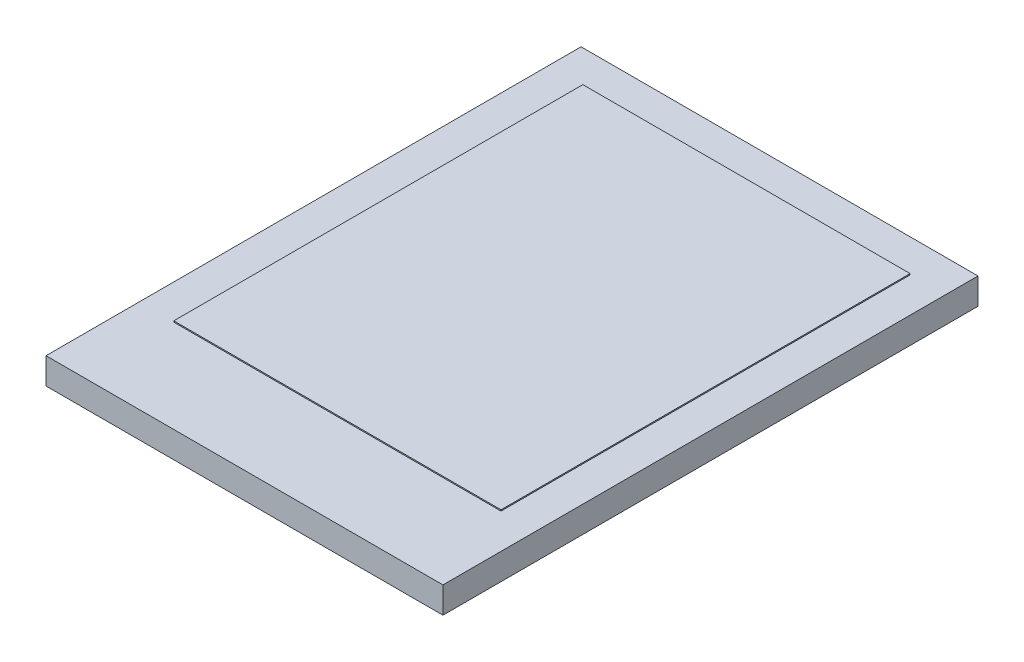
SolidWorks part; units mm, degrees
ref_plane "Спереди" through (0, 0, 0) normal (0, 0, 1) x (1, 0, 0)
ref_plane "Сверху" through (0, 0, 0) normal (0, 1, 0) x (1, 0, 0)
ref_plane "Справа" through (0, 0, 0) normal (1, 0, 0) x (0, 0, -1)
sketch "Эскиз1" plane through (0, 0, 0) normal (0, 1, 0) x (1, 0, 0)
  line L1 (-17, 22.915) -> (17, 22.915)
  line L2 (-17, 22.915) -> (-17, -22.915)
  line L3 (-17, -22.915) -> (17, -22.915)
  line L4 (17, 22.915) -> (17, -22.915)
  line L5 (-17, 22.915) -> (17, -22.915) construction
  line L6 (-17, -22.915) -> (17, 22.915) construction
  point P0 (0, 0)
  dimension "D1" = 34
  dimension "D2" = 45.83
extrude "Бобышка-Вытянуть1" add sketch "Эскиз1" along normal blind 2.25
sketch "Эскиз2" plane through (0, 2.25, 0) normal (0, 1, 0) x (1, 0, 0)
  line L0 (17, 22.915) -> (-17, 22.915) construction
  line L1 (-14.015, 20.085) -> (14.015, 20.085)
  line L2 (-14.015, 20.085) -> (-14.015, -14.955)
  line L3 (-14.015, -14.955) -> (14.015, -14.955)
  line L4 (14.015, 20.085) -> (14.015, -14.955)
  line L5 (-17, 22.915) -> (-17, -22.915) construction
  line L6 (17, -22.915) -> (17, 22.915) construction
  dimension "D1" = 2.83
  dimension "D2" = 35.04
  dimension "D3" = 28.03
  dimension "D4" = 2.985
  dimension "D5" = 2.985
extrude "Бобышка-Вытянуть2" add sketch "Эскиз2" along normal blind 0.1 contours L2 L1 L4 L3
sketch "Эскиз4" plane through (0, 0, 0) normal (0, -1, 0) x (1, 0, 0)
  line L0 (-19.7961, 12.665) -> (24.4396, 12.665) construction
  line L1 (18.8185, 10.6007) -> (18.8186, 10.6007) construction
  line L2 (-17, 22.915) -> (17, 22.915) construction
  line L3 (0, 26.4476) -> (0, -27.081) construction
  line L4 (-4.6, 14.4642) -> (-4.6, 12.6642)
  line L5 (-5.4, 14.4642) -> (-5, 14.4642)
  line L6 (-5.4, 14.4642) -> (-5.4, 12.6642)
  line L7 (-5.4, 12.6642) -> (-5, 12.6642)
  line L8 (-5, 14.4642) -> (-5, 12.6642)
  line L9 (-4.6, 14.4642) -> (-4.2, 14.4642)
  line L10 (-4.2, 14.4642) -> (-4.2, 12.6642)
  line L11 (-4.6, 12.6642) -> (-4.2, 12.6642)
  line L12 (-3.8, 14.4642) -> (-3.8, 12.6642)
  line L13 (-3.8, 14.4642) -> (-3.4, 14.4642)
  line L14 (-3.4, 14.4642) -> (-3.4, 12.6642)
  line L15 (-3.8, 12.6642) -> (-3.4, 12.6642)
  line L16 (-3, 14.4642) -> (-3, 12.6642)
  line L17 (-3, 14.4642) -> (-2.6, 14.4642)
  line L18 (-2.6, 14.4642) -> (-2.6, 12.6642)
  line L19 (-3, 12.6642) -> (-2.6, 12.6642)
  line L20 (-2.2, 14.4642) -> (-2.2, 12.6642)
  line L21 (-2.2, 14.4642) -> (-1.8, 14.4642)
  line L22 (-1.8, 14.4642) -> (-1.8, 12.6642)
  line L23 (-2.2, 12.6642) -> (-1.8, 12.6642)
  line L24 (-1.4, 14.4642) -> (-1.4, 12.6642)
  line L25 (-1.4, 14.4642) -> (-1, 14.4642)
  line L26 (-1, 14.4642) -> (-1, 12.6642)
  line L27 (-1.4, 12.6642) -> (-1, 12.6642)
  line L28 (-0.6, 14.4642) -> (-0.6, 12.6642)
  line L29 (-0.6, 14.4642) -> (-0.2, 14.4642)
  line L30 (-0.2, 14.4642) -> (-0.2, 12.6642)
  line L31 (-0.6, 12.6642) -> (-0.2, 12.6642)
  line L32 (0.2, 14.4642) -> (0.2, 12.6642)
  line L33 (0.2, 14.4642) -> (0.6, 14.4642)
  line L34 (0.6, 14.4642) -> (0.6, 12.6642)
  line L35 (0.2, 12.6642) -> (0.6, 12.6642)
  line L36 (1, 14.4642) -> (1, 12.6642)
  line L37 (1, 14.4642) -> (1.4, 14.4642)
  line L38 (1.4, 14.4642) -> (1.4, 12.6642)
  line L39 (1, 12.6642) -> (1.4, 12.6642)
  line L40 (1.8, 14.4642) -> (1.8, 12.6642)
  line L41 (1.8, 14.4642) -> (2.2, 14.4642)
  line L42 (2.2, 14.4642) -> (2.2, 12.6642)
  line L43 (1.8, 12.6642) -> (2.2, 12.6642)
  line L44 (2.6, 14.4642) -> (2.6, 12.6642)
  line L45 (2.6, 14.4642) -> (3, 14.4642)
  line L46 (3, 14.4642) -> (3, 12.6642)
  line L47 (2.6, 12.6642) -> (3, 12.6642)
  line L48 (3.4, 14.4642) -> (3.4, 12.6642)
  line L49 (3.4, 14.4642) -> (3.8, 14.4642)
  line L50 (3.8, 14.4642) -> (3.8, 12.6642)
  line L51 (3.4, 12.6642) -> (3.8, 12.6642)
  line L52 (4.2, 14.4642) -> (4.2, 12.6642)
  line L53 (4.2, 14.4642) -> (4.6, 14.4642)
  line L54 (4.6, 14.4642) -> (4.6, 12.6642)
  line L55 (4.2, 12.6642) -> (4.6, 12.6642)
  line L56 (5, 14.4642) -> (5, 12.6642)
  line L57 (5, 14.4642) -> (5.4, 14.4642)
  line L58 (5.4, 14.4642) -> (5.4, 12.6642)
  line L59 (5, 12.6642) -> (5.4, 12.6642)
  dimension "D1" = 10.25
  dimension "D2" = 0.4
  dimension "D3" = 1.8
  dimension "D4" = 5
  dimension "D5" = 14
extrude "Бобышка-Вытянуть3" add sketch "Эскиз4" along normal blind 0.1
